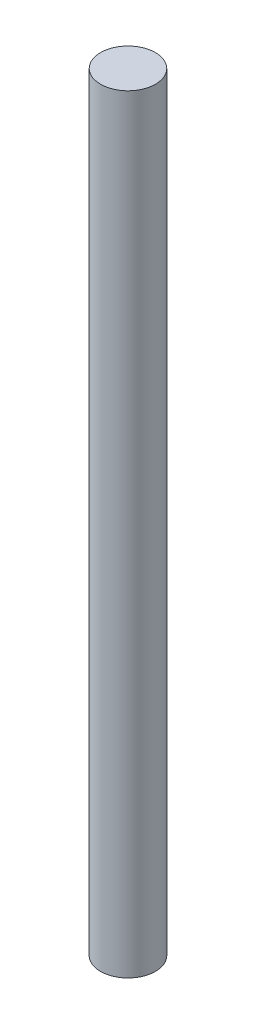
SolidWorks part; units mm, degrees
material "AISI 316 Stainless Steel Sheet (SS)"
ref_plane "Front Plane" through (0, 0, 0) normal (0, 0, 1) x (1, 0, 0)
ref_plane "Top Plane" through (0, 0, 0) normal (0, 1, 0) x (1, 0, 0)
ref_plane "Right Plane" through (0, 0, 0) normal (1, 0, 0) x (0, 0, -1)
sketch "Sketch1" plane through (0, 0, 0) normal (0, 1, 0) x (1, 0, 0)
  circle A0 centre (0, 0) radius 5
  dimension "D1" = 10
extrude "Boss-Extrude1" add sketch "Sketch1" along normal blind 140
